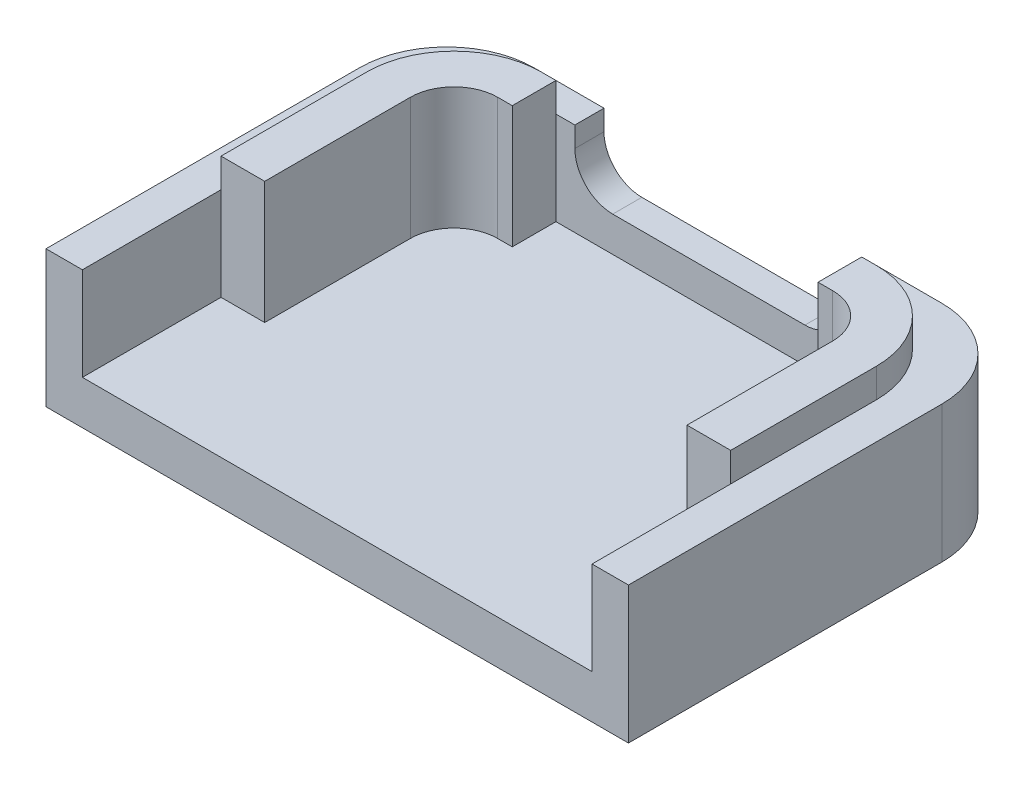
SolidWorks part; units mm, degrees
ref_plane "Front Plane" through (0, 0, 0) normal (0, 0, 1) x (1, 0, 0)
ref_plane "Top Plane" through (0, 0, 0) normal (0, 1, 0) x (1, 0, 0)
ref_plane "Right Plane" through (0, 0, 0) normal (1, 0, 0) x (0, 0, -1)
sketch "Sketch1" plane through (0, 0, 0) normal (0, 1, 0) x (1, 0, 0)
  line L5 (-1.5, 20.46) -> (-1.5, 9.7)
  line L7 (18.5, 20.46) -> (18.5, 9.7)
  line L9 (1.5, 23.46) -> (15.5, 23.46)
  line L13 (-1.5, 9.7) -> (18.5, 9.7)
  arc A2 (15.5, 23.46) -> (18.5, 20.46) centre (15.5, 20.46) cw
  arc A3 (1.5, 23.46) -> (-1.5, 20.46) centre (1.5, 20.46) ccw
  point P6 (-1.5, 23.96)
  point P7 (-1.5, -3.04)
  point P8 (18.5, -3.04)
  point P9 (18.5, 23.96)
  point P25 (17, 22.46)
  dimension "D1" = 13.76
sketch "Sketch2" plane through (0, 0, 0) normal (0, 1, 0) x (1, 0, 0)
  line L0 (2.75, 20.96) -> (3.25, 20.96)
  line L1 (2.75, 22.46) -> (3.25, 22.46)
  line L2 (-0.25, 19.46) -> (-0.25, 14.46)
  line L4 (17.25, 19.46) -> (17.25, 14.46)
  line L10 (1.25, 19.46) -> (1.25, 14.46)
  line L12 (15.75, 19.46) -> (15.75, 14.46)
  line L14 (-0.25, 14.46) -> (1.25, 14.46)
  line L15 (15.75, 14.46) -> (17.25, 14.46)
  line L16 (3.25, 20.96) -> (3.25, 22.46)
  line L17 (1.25, 19.46) -> (1.25, 9.9) construction
  line L18 (-0.25, 19.46) -> (-0.25, 8.4) construction
  line L23 (17.25, 8.4) -> (-0.25, 8.4) construction
  line L24 (15.75, 9.9) -> (1.25, 9.9) construction
  line L25 (15.75, 19.46) -> (15.75, 9.9) construction
  line L26 (17.25, 19.46) -> (17.25, 8.4) construction
  line L27 (2.75, 20.96) -> (14.25, 20.96) construction
  line L28 (13.75, 20.96) -> (13.75, 22.46)
  line L29 (13.75, 22.46) -> (14.25, 22.46)
  line L30 (13.75, 20.96) -> (14.25, 20.96)
  line L31 (2.75, 22.46) -> (14.25, 22.46) construction
  arc A4 (17.25, 19.46) -> (14.25, 22.46) centre (14.25, 19.46) ccw
  arc A7 (-0.25, 19.46) -> (2.75, 22.46) centre (2.75, 19.46) cw
  arc A8 (15.75, 19.46) -> (14.25, 20.96) centre (14.25, 19.46) ccw
  arc A9 (1.25, 19.46) -> (2.75, 20.96) centre (2.75, 19.46) cw
  point P6 (-1.5, 23.96)
  point P7 (-1.5, -3.04)
  point P8 (18.5, -3.04)
  point P9 (18.5, 23.96)
  point P25 (17.25, 22.46)
  dimension "D6" = 0.5
  dimension "D7" = 3
  dimension "D1" = 0.5
  dimension "D2" = 1.5
  dimension "D3" = 8
  dimension "D5" = 1.25
  dimension "D4" = 17.25
sketch "Sketch3" plane through (0, 0, 0) normal (0, 1, 0) x (1, 0, 0)
  line L1 (2.75, 22.46) -> (14.25, 22.46)
  line L2 (-0.25, 19.46) -> (-0.25, 9.7)
  line L4 (17.25, 19.46) -> (17.25, 9.7)
  line L5 (-1.5, 20.46) -> (-1.5, 9.7)
  line L7 (18.5, 20.46) -> (18.5, 9.7)
  line L9 (1.5, 23.46) -> (15.5, 23.46)
  line L10 (-1.5, -2.79) -> (18.5, -2.79) construction
  line L11 (-1.5, 23.71) -> (18.5, 23.71) construction
  line L12 (-1.5, 23.71) -> (-1.5, -2.79) construction
  line L13 (18.5, 23.71) -> (18.5, -2.79) construction
  line L14 (17.25, 22.46) -> (17.25, -1.54) construction
  line L15 (-0.25, 22.46) -> (17.25, 22.46) construction
  line L16 (-0.25, -1.54) -> (17.25, -1.54) construction
  line L17 (-0.25, 22.46) -> (-0.25, -1.54) construction
  line L18 (-0.25, 9.7) -> (-1.5, 9.7)
  line L21 (18.5, 9.7) -> (17.25, 9.7)
  arc A2 (15.5, 23.46) -> (18.5, 20.46) centre (15.5, 20.46) cw
  arc A3 (1.5, 23.46) -> (-1.5, 20.46) centre (1.5, 20.46) ccw
  arc A4 (17.25, 19.46) -> (14.25, 22.46) centre (14.25, 19.46) ccw
  arc A7 (-0.25, 19.46) -> (2.75, 22.46) centre (2.75, 19.46) cw
  point P25 (17.25, 22.46)
  dimension "D7" = 3
  dimension "D1" = 12.76
  dimension "D2" = 18.5
  dimension "D5" = 1
  dimension "D4" = 1.25
extrude "Boss-Extrude1" add sketch "Sketch1" against normal blind 1.5
extrude "Boss-Extrude2" add sketch "Sketch3" along normal blind 3.2
extrude "Boss-Extrude3" add sketch "Sketch2" along normal blind 4.2
ref_plane "Plane1" through (0, 0, -23.46) normal (0, 0, -1) x (-1, 0, 0)
sketch "Sketch5" plane through (0, 0, -23.46) normal (0, 0, -1) x (-1, 0, 0)
  line L0 (-15.5, 3.2) -> (-1.5, 3.2) construction
  line L1 (-13.1, 3.2) -> (-3.9, 3.2)
  line L2 (-13.1, 3.2) -> (-13.1, 2.5)
  line L3 (-11.8, 1.2) -> (-5.2, 1.2)
  line L4 (-3.9, 3.2) -> (-3.9, 2.5)
  arc A0 (-5.2, 1.2) -> (-3.9, 2.5) centre (-5.2, 2.5) ccw
  arc A1 (-13.1, 2.5) -> (-11.8, 1.2) centre (-11.8, 2.5) ccw
  point P4 (-8.5, 1.2)
  point P7 (-8.5, 3.2)
  point P10 (-3.9, 1.2)
  point P13 (-13.1, 1.2)
  dimension "D5" = 1.3
  dimension "D1" = 0
  dimension "D2" = 9.2
  dimension "D3" = 0
  dimension "D4" = 2
extrude "Cut-Extrude1" cut sketch "Sketch5" against normal through all
